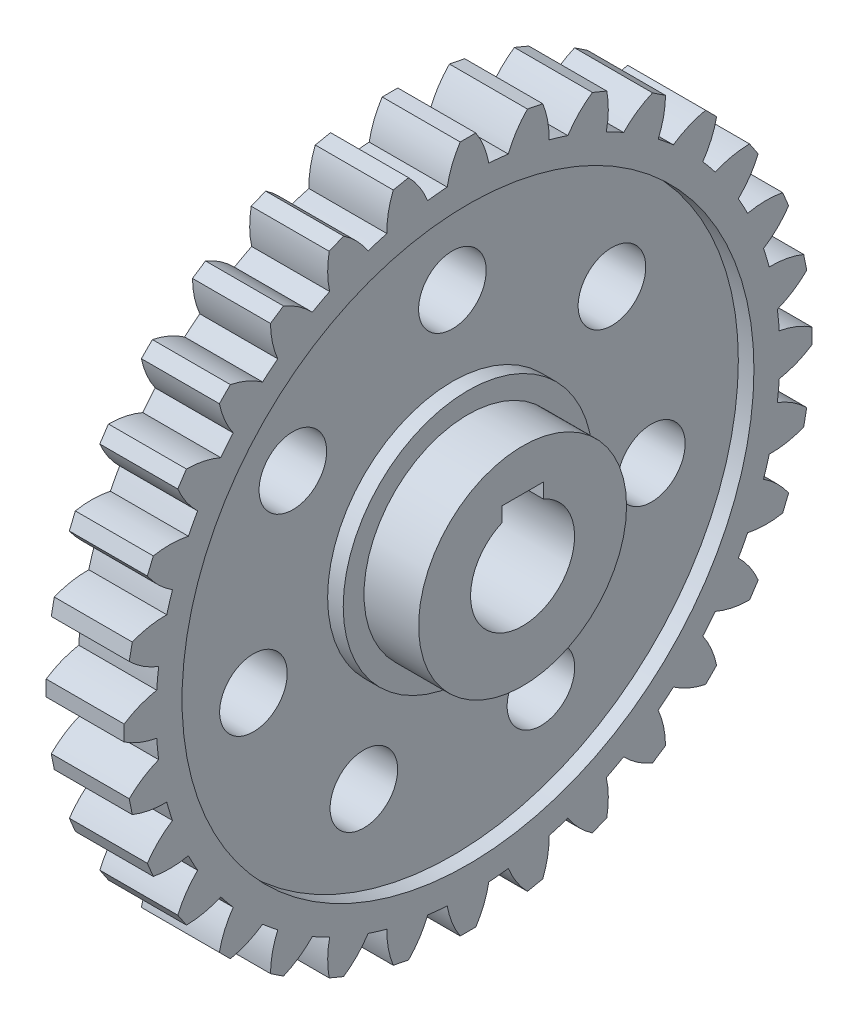
SolidWorks part; units mm, degrees
ref_plane "Front Plane" through (0, 0, 0) normal (0, 0, 1) x (1, 0, 0)
ref_plane "Top Plane" through (0, 0, 0) normal (0, 1, 0) x (1, 0, 0)
ref_plane "Right Plane" through (0, 0, 0) normal (1, 0, 0) x (0, 0, -1)
sketch "Sketch2" plane through (0, 0, 0) normal (1, 0, 0) x (0, 0, -1)
  circle A0 centre (0, 0) radius 60
  dimension "D1" = 120
extrude "Boss-Extrude1" add sketch "Sketch2" along normal mid plane 15
sketch "Sketch3" plane through (7.5, 0, 0) normal (1, 0, 0) x (0, 0, -1)
  line L0 (0, 0) -> (0, 67.0398) construction
  line L1 (-1.5, 66.1335) -> (1.5, 66.1335)
  arc A0 (-4, 59.8665) -> (4, 59.8665) centre (0, 0) cw
  circle A1 centre (0, 0) radius 60 construction
  arc A2 (-1.5, 66.1335) -> (-4, 59.8665) centre (12.726, 56.8264) ccw
  arc A3 (1.5, 66.1335) -> (4, 59.8665) centre (-12.726, 56.8264) cw
  dimension "D1" = 1.5
  dimension "D4" = 17
  dimension "D2" = 6.267
  dimension "D3" = 4
extrude "Boss-Extrude2" add sketch "Sketch3" against normal up to surface (15 mm away) up to face at (-7.5, 0, -60)
pattern_circular "CirPattern1" count 32 over 360 about axis through (0, 0, 0) along (1, 0, 0) of "Boss-Extrude2"
sketch "Sketch5" plane through (0, 0, 0) normal (1, 0, 0) x (0, 0, -1)
  circle A0 centre (0, 0) radius 20
  dimension "D1" = 40
extrude "Boss-Extrude4" add sketch "Sketch5" along normal mid plane 36
sketch "Sketch6" plane through (18, 0, 0) normal (1, 0, 0) x (0, 0, -1)
  line L0 (0, 0) -> (0, 12) construction
  line L1 (-4, 12) -> (4, 12)
  line L2 (-4, 12) -> (-4, 9.1652)
  line L3 (4, 12) -> (4, 9.1652)
  arc A0 (-4, 9.1652) -> (4, 9.1652) centre (0, 0) ccw
  dimension "D1" = 20
  dimension "D2" = 12
  dimension "D3" = 8
extrude "Cut-Extrude1" cut sketch "Sketch6" against normal through all
sketch "Sketch7" plane through (7.5, 0, 0) normal (1, 0, 0) x (0, 0, -1)
  circle A0 centre (0, 0) radius 55
  circle A1 centre (0, 0) radius 24
  dimension "D1" = 110
  dimension "D2" = 48
extrude "Cut-Extrude2" cut sketch "Sketch7" against normal blind 3
sketch "Sketch8" plane through (4.5, 0, 0) normal (1, 0, 0) x (0, 0, -1)
  circle A0 centre (0, 0) radius 39.25 construction
  circle A1 centre (0, 39.25) radius 6.5
  circle A2 centre (30.6869, 24.472) radius 6.5
  circle A3 centre (38.2659, -8.7339) radius 6.5
  circle A4 centre (17.0299, -35.363) radius 6.5
  circle A5 centre (-17.0299, -35.363) radius 6.5
  circle A6 centre (-38.2659, -8.7339) radius 6.5
  circle A7 centre (-30.6869, 24.472) radius 6.5
  point P19 (0, 0)
  dimension "D1" = 78.5
  dimension "D2" = 13
  dimension "D3" = 7
extrude "Cut-Extrude3" cut sketch "Sketch8" against normal through all
